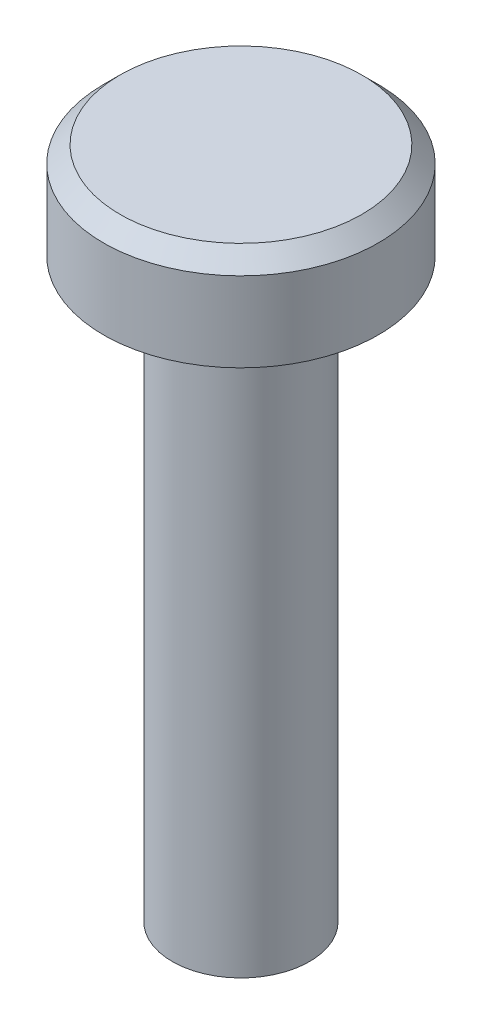
SolidWorks part; units mm, degrees
ref_plane "Front Plane" through (0, 0, 0) normal (0, 0, 1) x (1, 0, 0)
ref_plane "Top Plane" through (0, 0, 0) normal (0, 1, 0) x (1, 0, 0)
ref_plane "Right Plane" through (0, 0, 0) normal (1, 0, 0) x (0, 0, -1)
sketch "Sketch1" plane through (0, 0, 0) normal (0, 0, 1) x (1, 0, 0)
  line L0 (0, 0) -> (4.4, 0)
  line L1 (5, -0.6) -> (5, -3.5)
  line L2 (5, -3.5) -> (2.5, -3.5)
  line L3 (2.5, -3.5) -> (2.5, -24.5)
  line L4 (2.5, -24.5) -> (0, -24.5)
  line L5 (0, 0) -> (0, -24.5) construction
  line L6 (0, 0) -> (0, -24.5)
  line L7 (4.4, 0) -> (5, -0.6)
  point P1 (5, 0)
  dimension "D1" = 2.5
  dimension "D2" = 3.5
  dimension "D3" = 5
  dimension "D4" = 21
revolve "Revolve1" add sketch "Sketch1" angle 360 about L5
